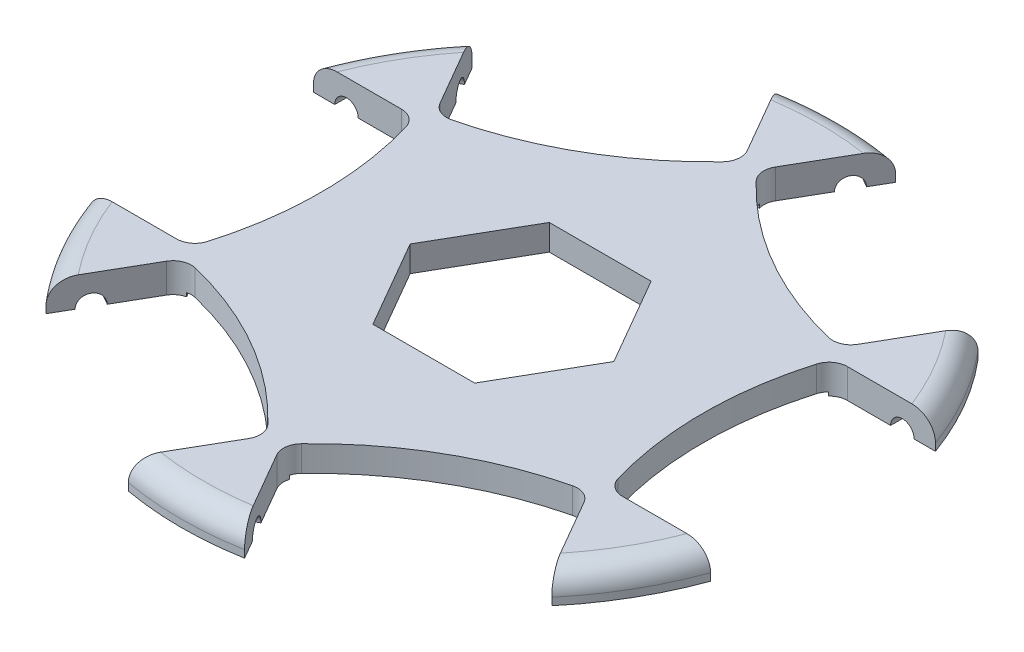
SolidWorks part; units mm, degrees
other "Markierung1"
sketch "Skizze8"
ref_plane "Ebene vorne" through (0, 0, 0) normal (0, 0, 1) x (1, 0, 0)
ref_plane "Ebene oben" through (0, 0, 0) normal (0, 1, 0) x (1, 0, 0)
ref_plane "Ebene rechts" through (0, 0, 0) normal (1, 0, 0) x (0, 0, -1)
sketch "Skizze1" plane through (0, 0, 0) normal (0, 1, 0) x (1, 0, 0)
  circle A0 centre (0, 0) radius 45
  dimension "D1" = 90
extrude "Aufsatz-Linear austragen1" add sketch "Skizze1" along normal blind 4
sketch "Skizze2" plane through (0, 4, 0) normal (0, 1, 0) x (1, 0, 0)
  line L0 (-28.5037, 15.3) -> (-71.0776, 15.3)
  line L1 (-28.5037, -15.3) -> (-71.0776, -15.3)
  line L2 (-71.0776, 15.3) -> (-71.0776, -15.3)
  circle A0 centre (-74, 0) radius 48
  circle M2 centre (0, 0) radius 45
  dimension "D1" = 74
  dimension "D2" = 96
  dimension "D3" = 30.6
  dimension "D4" = 15.3
extrude "Schnitt-Linear austragen2" cut sketch "Skizze2" against normal blind 10 contours L1 A0 L0 M2
pattern_circular "Kreismuster1" count 6 over 360 about axis through (0, 0, 0) along (0, 1, 0) of "Schnitt-Linear austragen2"
sketch "Skizze3" plane through (0, 0, 0) normal (0, -1, 0) x (1, 0, 0)
  line L1 (13.8564, 0) -> (6.9282, 12)
  line L2 (6.9282, 12) -> (-6.9282, 12)
  line L3 (-6.9282, 12) -> (-13.8564, 0)
  line L4 (-13.8564, 0) -> (-6.9282, -12)
  line L5 (-6.9282, -12) -> (6.9282, -12)
  line L6 (6.9282, -12) -> (13.8564, 0)
  circle A0 centre (0, 0) radius 12 construction
  dimension "D1" = 24
extrude "Schnitt-Linear austragen3" cut sketch "Skizze3" against normal blind 10
fillet "Verrundung1" radius 2.5 12 edges at (-28.5037, 2, 15.3) (-1.0017, 2, 32.335) (1.0017, 2, 32.335) (27.5021, 2, 17.035) (28.5037, 2, 15.3) (28.5037, 2, -15.3) (27.5021, 2, -17.035) (1.0017, 2, -32.335) (-1.0017, 2, -32.335) (-27.5021, 2, -17.035) (-28.5037, 2, -15.3) (-27.5021, 2, 17.035)
sketch "Skizze4" [suppressed] plane through (0, 4, 0) normal (0, 1, 0) x (1, 0, 0)
  circle A0 centre (0, 0) radius 21.0071
sketch "Skizze5" plane through (13.2502, 0, 7.65) normal (-0.866, 0, -0.5) x (-0.5, 0, 0.866)
  line L0 (-30.3375, 0) -> (-42.3191, 0) construction
  line L1 (-42.3191, 0) -> (-42.3191, 4) construction
  circle A0 centre (-37.8191, 0) radius 1.6
  dimension "D1" = 4.5
extrude "Schnitt-Linear austragen5" cut sketch "Skizze5" against normal blind 3.8 contours A0
fillet "Verrundung6" radius 0.5 1 edges at (35.4507, 1.6, -23.2023)
pattern_circular "Kreismuster2" count 6 over 360 about axis through (0, 0, 0) along (0, 1, 0) of "Schnitt-Linear austragen5", "Verrundung6"
sketch "Skizze6" plane through (0, 0, -15.3) normal (0, 0, 1) x (1, 0, 0)
  line L0 (30.3375, 0) -> (42.3191, 0) construction
  line L1 (42.3191, 0) -> (42.3191, 4) construction
  circle A0 centre (37.8191, 0) radius 1.6
  dimension "D1" = 4.5
extrude "Schnitt-Linear austragen6" cut sketch "Skizze6" against normal blind 3.8
fillet "Verrundung7" radius 0.5 1 edges at (37.8191, 1.6, -19.1)
pattern_circular "Kreismuster3" count 6 over 360 about axis through (0, 0, 0) along (0, 1, 0) of "Schnitt-Linear austragen6", "Verrundung7"
sketch "Skizze7" plane through (0, 0, 0) normal (0, -1, 0) x (1, 0, 0)
  circle A0 centre (0, 0) radius 32
extrude "Schnitt-Linear austragen7" cut sketch "Skizze7" against normal blind 0.5
fillet "Verrundung2" radius 3 6 edges at (-38.9711, 4, 22.5) (0, 4, 45) (38.9711, 4, 22.5) (38.9711, 4, -22.5) (0, 4, -45) (-38.9711, 4, -22.5)
sketch "Zentrierung" plane through (0, 0.5, 0) normal (0, -1, 0) x (1, 0, 0)
  circle A0 centre (0, 0) radius 20
